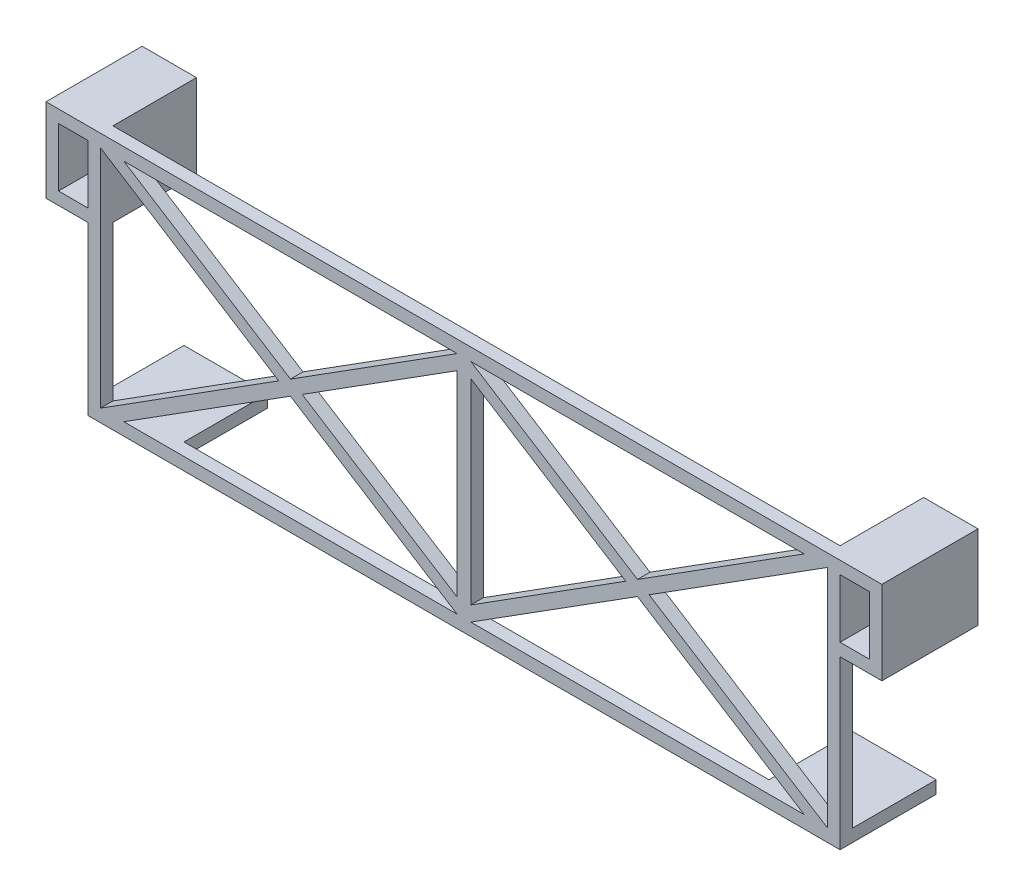
SolidWorks part; units mm, degrees
ref_plane "Alzado" through (0, 0, 0) normal (0, 0, 1) x (1, 0, 0)
ref_plane "Planta" through (0, 0, 0) normal (0, 1, 0) x (1, 0, 0)
ref_plane "Vista lateral" through (0, 0, 0) normal (1, 0, 0) x (0, 0, -1)
sketch "Croquis1" plane through (0, 0, 0) normal (0, 0, 1) x (1, 0, 0)
  line L0 (-211.8473, 44.9032) -> (-211.8473, -9.0968)
  line L1 (-214.8473, 47.9032) -> (-34.8473, 47.9032)
  line L2 (-214.8473, 47.9032) -> (-214.8473, -12.0968)
  line L3 (-214.8473, -12.0968) -> (-34.8473, -12.0968)
  line L4 (-34.8473, 47.9032) -> (-34.8473, -12.0968)
  line L5 (-211.8473, -9.0968) -> (-206.2357, -9.0968) construction
  line L6 (-206.2357, -9.0968) -> (-126.4857, -9.0968)
  line L7 (-206.2357, 44.9032) -> (-126.4857, 44.9032)
  line L8 (-211.8473, 44.9032) -> (-126.4857, -9.0968) construction
  line L9 (-211.8473, -9.0968) -> (-126.4857, 44.9032) construction
  line L10 (-211.8473, 44.9032) -> (-169.1665, 17.9032)
  line L11 (-169.1665, 17.9032) -> (-211.8473, -9.0968)
  line L12 (-206.2357, -9.0968) -> (-166.3607, 16.1283)
  line L13 (-166.3607, 16.1283) -> (-126.4857, -9.0968)
  line L14 (-206.2357, 44.9032) -> (-166.3607, 19.6782)
  line L15 (-166.3607, 19.6782) -> (-126.4857, 44.9032)
  line L19 (-166.3607, 19.6782) -> (-125.3878, -6.2414) construction
  line L20 (-166.3607, 16.1283) -> (-125.3878, 42.0479) construction
  line L21 (-126.4857, -9.0968) -> (-126.4857, 44.9032) construction
  line L22 (-126.4857, 41.3533) -> (-126.4857, -5.5469)
  line L23 (-126.4857, -5.5469) -> (-163.5549, 17.9032)
  line L24 (-163.5549, 17.9032) -> (-126.4857, 41.3533)
  line L25 (-124.8473, -12.0968) -> (-124.8473, 47.9032) construction
  line L26 (-123.2088, -9.0968) -> (-123.2088, 44.9032) construction
  line L27 (-83.3338, 16.1283) -> (-124.3067, 42.0479) construction
  line L28 (-83.3338, 19.6782) -> (-124.3067, -6.2414) construction
  line L29 (-37.8473, -9.0968) -> (-123.2088, 44.9032) construction
  line L30 (-37.8473, 44.9032) -> (-123.2088, -9.0968) construction
  line L31 (-37.8473, -9.0968) -> (-43.4588, -9.0968) construction
  line L32 (-86.1396, 17.9032) -> (-123.2088, 41.3533)
  line L33 (-123.2088, -5.5469) -> (-86.1396, 17.9032)
  line L34 (-123.2088, 41.3533) -> (-123.2088, -5.5469)
  line L35 (-83.3338, 19.6782) -> (-123.2088, 44.9032)
  line L36 (-43.4588, 44.9032) -> (-83.3338, 19.6782)
  line L37 (-83.3338, 16.1283) -> (-123.2088, -9.0968)
  line L38 (-43.4588, -9.0968) -> (-83.3338, 16.1283)
  line L39 (-80.528, 17.9032) -> (-37.8473, -9.0968)
  line L40 (-37.8473, 44.9032) -> (-80.528, 17.9032)
  line L41 (-43.4588, 44.9032) -> (-123.2088, 44.9032)
  line L42 (-43.4588, -9.0968) -> (-123.2088, -9.0968)
  line L43 (-34.8473, 47.9032) -> (-34.8473, -12.0968)
  line L44 (-37.8473, 44.9032) -> (-37.8473, -9.0968)
  dimension "D1" = 180
  dimension "D2" = 60
  dimension "D3" = 3
  dimension "D4" = 3
  dimension "D5" = 3
  dimension "D6" = 3
  dimension "D7" = 79.75
  dimension "D8" = 3
extrude "Saliente-Extruir1" add sketch "Croquis1" along normal blind 3 contours L4 L1 L2 L3 L41 L36 L35 L34 L32 L33 L15 L14 L7 L10 L11 L0 L12 L13 L6 L23 L24 L22 L38 L42 L37 L40 L44 L39
sketch "Croquis2" plane through (0, 0, 3) normal (0, 0, 1) x (1, 0, 0)
  line L0 (-206.2357, -9.0968) -> (-126.4857, -9.0968) construction
  line L1 (-214.8473, -12.0968) -> (-194.8473, -12.0968)
  line L2 (-214.8473, -12.0968) -> (-214.8473, -9.0968)
  line L3 (-214.8473, -9.0968) -> (-194.8473, -9.0968)
  line L4 (-194.8473, -12.0968) -> (-194.8473, -9.0968)
  line L10 (-124.8473, -12.0968) -> (-124.8473, 47.9032) construction
  line L11 (-214.8473, -12.0968) -> (-34.8473, -12.0968) construction
  line L12 (-214.8473, 47.9032) -> (-34.8473, 47.9032) construction
  line L21 (-211.8473, 44.9032) -> (-211.8473, -9.0968) construction
  line L22 (-211.8473, 47.9032) -> (-224.8473, 47.9032)
  line L23 (-211.8473, 47.9032) -> (-211.8473, 27.9032)
  line L24 (-211.8473, 27.9032) -> (-224.8473, 27.9032)
  line L25 (-224.8473, 47.9032) -> (-224.8473, 27.9032)
  line L26 (-214.8473, 47.9032) -> (-214.8473, -12.0968) construction
  line L27 (-221.8473, 44.9032) -> (-214.8473, 44.9032)
  line L28 (-221.8473, 44.9032) -> (-221.8473, 30.9032)
  line L29 (-221.8473, 30.9032) -> (-214.8473, 30.9032)
  line L30 (-214.8473, 44.9032) -> (-214.8473, 30.9032)
  line L31 (-34.8473, 44.9032) -> (-34.8473, 30.9032)
  line L32 (-27.8473, 30.9032) -> (-34.8473, 30.9032)
  line L33 (-27.8473, 44.9032) -> (-27.8473, 30.9032)
  line L34 (-27.8473, 44.9032) -> (-34.8473, 44.9032)
  line L35 (-24.8473, 47.9032) -> (-24.8473, 27.9032)
  line L36 (-37.8473, 27.9032) -> (-24.8473, 27.9032)
  line L37 (-37.8473, 47.9032) -> (-37.8473, 27.9032)
  line L38 (-37.8473, 47.9032) -> (-24.8473, 47.9032)
  line L39 (-54.8473, -12.0968) -> (-54.8473, -9.0968)
  line L40 (-34.8473, -9.0968) -> (-54.8473, -9.0968)
  line L41 (-34.8473, -12.0968) -> (-34.8473, -9.0968)
  line L42 (-34.8473, -12.0968) -> (-54.8473, -12.0968)
  dimension "D1" = 20
  dimension "D2" = 20
  dimension "D3" = 13
  dimension "D4" = 0
  dimension "D5" = 3
  dimension "D6" = 3
  dimension "D7" = 3
extrude "Saliente-Extruir2" add sketch "Croquis2" against normal blind 23
